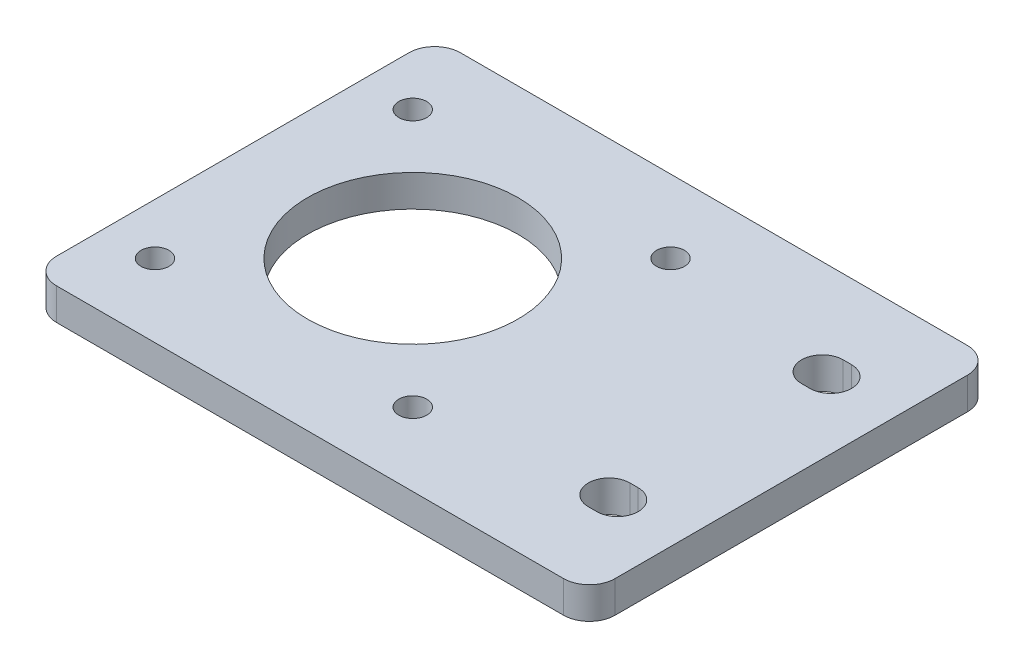
SolidWorks part; units mm, degrees
material "1060 Alloy"
ref_plane "Front Plane" through (0, 0, 0) normal (0, 0, 1) x (1, 0, 0)
ref_plane "Top Plane" through (0, 0, 0) normal (0, 1, 0) x (1, 0, 0)
ref_plane "Right Plane" through (0, 0, 0) normal (1, 0, 0) x (0, 0, -1)
sketch "Sketch1" plane through (0, 0, 0) normal (0, 1, 0) x (1, 0, 0)
  line L0 (-16.853, 10.7776) -> (51.4975, 10.7776) construction
  line L1 (-16.853, -12.7224) -> (48.147, -12.7224)
  line L2 (-16.853, -12.7224) -> (-16.853, 34.2776)
  line L3 (-16.853, 34.2776) -> (48.147, 34.2776)
  line L4 (48.147, -12.7224) -> (48.147, 34.2776)
  line L5 (39.357, -1.6324) -> (40.337, -1.6324) construction
  line L6 (39.357, 0.7776) -> (40.337, 0.7776)
  line L7 (39.357, -4.0424) -> (40.337, -4.0424)
  line L8 (39.357, 23.1876) -> (40.337, 23.1876) construction
  line L9 (39.357, 20.7776) -> (40.337, 20.7776)
  line L10 (39.357, 25.5976) -> (40.337, 25.5976)
  circle A0 centre (4.097, 10.7776) radius 12.25
  circle A1 centre (-10.903, -4.2224) radius 1.6238
  circle A2 centre (19.097, -4.2224) radius 1.6238
  circle A3 centre (19.097, 25.7776) radius 1.6238
  circle A4 centre (-10.903, 25.7776) radius 1.6238
  arc A5 (39.357, 0.7776) -> (39.357, -4.0424) centre (39.357, -1.6324) ccw
  arc A6 (40.337, -4.0424) -> (40.337, 0.7776) centre (40.337, -1.6324) ccw
  arc A7 (39.357, 20.7776) -> (39.357, 25.5976) centre (39.357, 23.1876) cw
  arc A8 (40.337, 25.5976) -> (40.337, 20.7776) centre (40.337, 23.1876) cw
  point P10 (39.847, -1.6324)
  point P23 (36.947, -1.6324)
  point P24 (42.747, -1.6324)
  point P28 (39.847, 23.1876)
  dimension "D3" = 24.5
  dimension "D1" = 65
  dimension "D2" = 47
  dimension "D4" = 20.95
  dimension "D5" = 15
  dimension "D6" = 15
  dimension "D9" = 4.82
  dimension "D10" = 5.8
  dimension "D11" = 5.4
  dimension "D12" = 20
  dimension "D7" = 2
  dimension "D8" = 2
extrude "Boss-Extrude1" add sketch "Sketch1" along normal blind 3.7
fillet "Fillet1" radius 3 4 edges at (-16.853, 1.85, -34.2776) (48.147, 1.85, -34.2776) (-16.853, 1.85, 12.7224) (48.147, 1.85, 12.7224)
